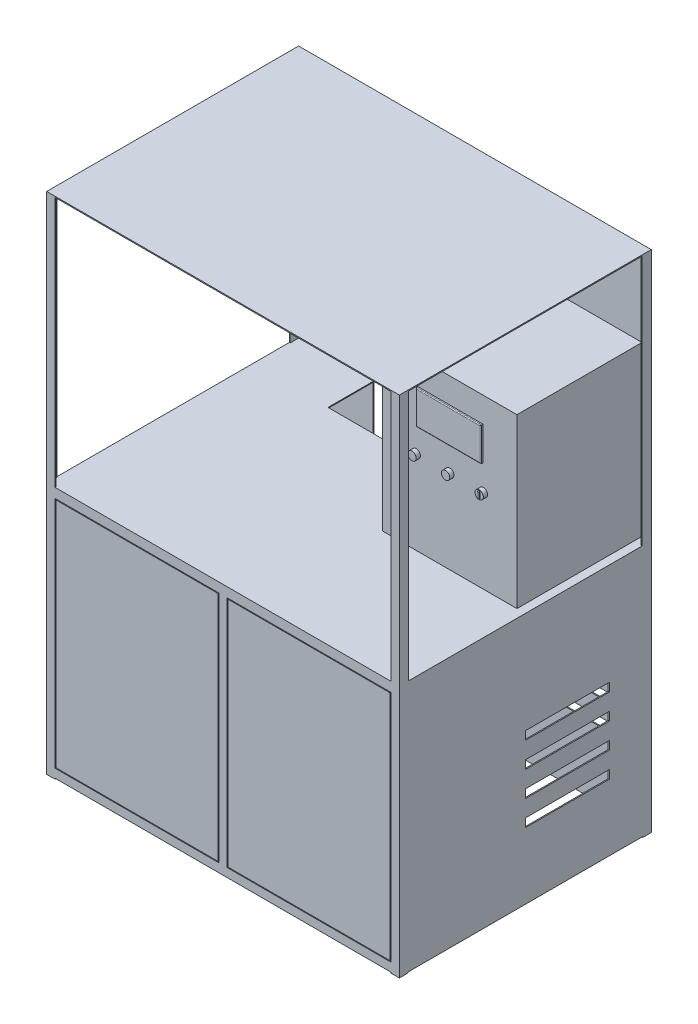
SolidWorks part; units mm, degrees
ref_plane "Front Plane" through (0, 0, 0) normal (0, 0, 1) x (1, 0, 0)
ref_plane "Top Plane" through (0, 0, 0) normal (0, 1, 0) x (1, 0, 0)
ref_plane "Right Plane" through (0, 0, 0) normal (1, 0, 0) x (0, 0, -1)
sketch "Sketch1" plane through (0, 0, 0) normal (0, 1, 0) x (1, 0, 0)
  line L1 (533.4, 381) -> (-533.4, 381)
  line L2 (533.4, 381) -> (533.4, -381)
  line L3 (533.4, -381) -> (-533.4, -381)
  line L4 (-533.4, 381) -> (-533.4, -381)
  line L5 (533.4, 381) -> (-533.4, -381) construction
  line L6 (533.4, -381) -> (-533.4, 381) construction
  point P0 (0, 0)
  dimension "D1" = 762
  dimension "D2" = 1066.8
extrude "Boss-Extrude1" add sketch "Sketch1" along normal blind 2.54 contours L1 L4 L3 L2
sketch "Sketch2" plane through (0, 2.54, 0) normal (0, 1, 0) x (1, 0, 0)
  line L0 (533.4, 381) -> (-533.4, 381) construction
  line L1 (-304.8, 381) -> (-101.6, 381)
  line L2 (-304.8, 381) -> (-304.8, 241.3)
  line L3 (-304.8, 241.3) -> (-101.6, 241.3)
  line L4 (-101.6, 381) -> (-101.6, 241.3)
  line L5 (-533.4, 381) -> (-533.4, -381) construction
  dimension "D1" = 139.7
  dimension "D2" = 203.2
  dimension "D3" = 228.6
extrude "Cut-Extrude1" cut sketch "Sketch2" against normal through all contours L3 L4 L1 L2
sketch "Sketch3" plane through (0, 0, 0) normal (0, -1, 0) x (1, 0, 0)
  line L1 (-533.4, 381) -> (-508, 381)
  line L2 (-533.4, 381) -> (-533.4, 355.6)
  line L3 (-533.4, 355.6) -> (-508, 355.6)
  line L4 (-508, 381) -> (-508, 355.6)
  line L5 (533.4, 381) -> (508, 381)
  line L6 (533.4, 381) -> (533.4, 355.6)
  line L7 (533.4, 355.6) -> (508, 355.6)
  line L8 (508, 381) -> (508, 355.6)
  line L9 (533.4, -381) -> (508, -381)
  line L10 (533.4, -381) -> (533.4, -355.6)
  line L11 (533.4, -355.6) -> (508, -355.6)
  line L12 (508, -381) -> (508, -355.6)
  line L13 (-533.4, -381) -> (-508, -381)
  line L14 (-533.4, -381) -> (-533.4, -355.6)
  line L15 (-533.4, -355.6) -> (-508, -355.6)
  line L16 (-508, -381) -> (-508, -355.6)
  dimension "D1" = 25.4
extrude "Boss-Extrude2" add sketch "Sketch3" along normal blind 762
sketch "Sketch4" plane through (0, 2.54, 0) normal (0, 1, 0) x (1, 0, 0)
  line L0 (533.4, 381) -> (-101.6, 381) construction
  line L5 (101.6, 381) -> (508, 381)
  line L6 (101.6, 381) -> (101.6, 0)
  line L7 (101.6, 0) -> (508, 0)
  line L8 (508, 381) -> (508, 0)
  line L9 (533.4, 381) -> (533.4, -381) construction
  dimension "D1" = 25.4
  dimension "D2" = 406.4
  dimension "D3" = 381
extrude "Boss-Extrude3" add sketch "Sketch4" along normal blind 508
sketch "Sketch5" plane through (0, 0, 0) normal (0, 0, 1) x (1, 0, 0)
  line L0 (101.6, 510.54) -> (101.6, 2.54) construction
  line L1 (101.6, 2.54) -> (508, 2.54) construction
  circle A0 centre (203.2, 256.54) radius 12.7
  circle A1 centre (304.8, 256.54) radius 12.7
  circle A2 centre (406.4, 256.54) radius 12.7
  dimension "D1" = 25.4
  dimension "D5" = 101.6
  dimension "D2" = 101.6
  dimension "D3" = 254
  dimension "D4" = 3
extrude "Boss-Extrude4" add sketch "Sketch5" along normal blind 12.7
sketch "Sketch6" plane through (0, 0, 12.7) normal (0, 0, 1) x (1, 0, 0)
  line L0 (406.4, 269.24) -> (406.4, 243.84) construction
  line L1 (404.4262, 266.7336) -> (408.3738, 266.7336)
  line L2 (408.3738, 266.7336) -> (408.3738, 246.4676)
  line L3 (408.3738, 246.4676) -> (404.4262, 246.4676)
  line L4 (404.4262, 266.7336) -> (404.4262, 246.4676)
  circle A0 centre (406.4, 256.54) radius 12.7 construction
  circle A1 centre (406.4, 256.54) radius 12.7 construction
  point P9 (0, 0)
  point P12 (0, 0)
  point P14 (406.4, 246.4676)
  point P15 (406.4, 266.7336)
  dimension "D1" = 2.5064
  dimension "D2" = 2.6276
  dimension "D3" = 1.9738
extrude "Boss-Extrude5" add sketch "Sketch6" along normal blind 3.175
fillet "Fillet1" radius 2.54 1 edges at (406.4, 266.7336, 15.875)
sketch "Sketch7" plane through (0, 0, 0) normal (0, 0, 1) x (1, 0, 0)
  line L0 (101.6, 510.54) -> (101.6, 2.54) construction
  line L1 (208.3389, 434.34) -> (405.1889, 434.34)
  line L2 (208.3389, 434.34) -> (208.3389, 332.74)
  line L3 (208.3389, 332.74) -> (405.1889, 332.74)
  line L4 (405.1889, 434.34) -> (405.1889, 332.74)
  line L5 (101.6, 510.54) -> (508, 510.54) construction
  dimension "D1" = 106.7389
  dimension "D2" = 76.2
  dimension "D3" = 101.6
  dimension "D4" = 196.85
extrude "Boss-Extrude6" add sketch "Sketch7" along normal blind 6.35
fillet "Fillet2" radius 2.54 4 edges at (208.3389, 383.54, 6.35) (306.7639, 332.74, 6.35) (405.1889, 383.54, 6.35) (306.7639, 434.34, 6.35)
sketch "Sketch8" plane through (0, 2.54, 0) normal (0, 1, 0) x (1, 0, 0)
  line L0 (-304.8, 381) -> (-304.8, 241.3) construction
  line L1 (-533.4, 381) -> (-304.8, 381)
  line L2 (-533.4, 381) -> (-533.4, 378.46)
  line L3 (-530.86, 378.46) -> (-304.8, 378.46)
  line L4 (-304.8, 381) -> (-304.8, 378.46)
  line L5 (533.4, 381) -> (533.4, -381) construction
  line L6 (-101.6, 381) -> (533.4, 381)
  line L7 (-101.6, 381) -> (-101.6, 378.46)
  line L8 (-101.6, 378.46) -> (533.4, 378.46)
  line L9 (533.4, 381) -> (533.4, 378.46)
  line L10 (0, -381) -> (0, 381) construction
  line L11 (-533.4, 378.46) -> (-530.86, 378.46)
  line L12 (-533.4, 378.46) -> (-533.4, 353.06)
  line L13 (-533.4, 353.06) -> (-530.86, 353.06)
  line L14 (-530.86, 378.46) -> (-530.86, 353.06)
  line L15 (533.4, -381) -> (-533.4, -381) construction
  line L16 (-533.4, 0) -> (533.4, 0) construction
  line L17 (-533.4, 381) -> (-533.4, -381) construction
  line L18 (530.86, 378.46) -> (530.86, 353.06)
  line L19 (-533.4, -381) -> (-508, -381)
  line L20 (-533.4, -381) -> (-533.4, -378.46)
  line L21 (-533.4, -378.46) -> (-508, -378.46)
  line L22 (-508, -381) -> (-508, -378.46)
  line L23 (-533.4, -353.06) -> (-530.86, -353.06)
  line L24 (-533.4, -353.06) -> (-533.4, -378.46)
  line L25 (-533.4, -378.46) -> (-530.86, -378.46)
  line L26 (-530.86, -353.06) -> (-530.86, -378.46)
  line L27 (533.4, 353.06) -> (530.86, 353.06)
  line L28 (533.4, 378.46) -> (533.4, 353.06)
  line L29 (533.4, 378.46) -> (530.86, 378.46)
  line L30 (533.4, 381) -> (533.4, 378.46)
  line L31 (530.86, -353.06) -> (530.86, -378.46)
  line L32 (533.4, -378.46) -> (530.86, -378.46)
  line L33 (533.4, -353.06) -> (533.4, -378.46)
  line L34 (533.4, -353.06) -> (530.86, -353.06)
  line L35 (508, -381) -> (508, -378.46)
  line L36 (533.4, -378.46) -> (508, -378.46)
  line L37 (533.4, -381) -> (533.4, -378.46)
  line L38 (533.4, -381) -> (508, -381)
  point P44 (0, 0)
  line M9 (101.6, 0) -> (101.6, 381)
  line M10 (101.6, 381) -> (-101.6, 381)
  line M11 (-101.6, 381) -> (-101.6, 241.3)
  line M13 (-304.8, 241.3) -> (-304.8, 381)
  line M14 (-304.8, 381) -> (-533.4, 381)
  line M15 (-533.4, 381) -> (-533.4, -381)
  line M16 (-533.4, -381) -> (533.4, -381)
  line M17 (533.4, -381) -> (533.4, 381)
  line M18 (533.4, 381) -> (508, 381)
  line M19 (508, 381) -> (508, 0)
  dimension "D1" = 2.54
  dimension "D2" = 25.4
  dimension "D3" = 2.54
  dimension "D4" = 25.4
  dimension "D5" = 25.4
extrude "Boss-Extrude7" add sketch "Sketch8" along normal blind 759.46 contours L11 L3 M15 M13 M14 | L14 L11 L13 M15 | L8 M19 M17 M18 | L27 L8 L18 M17 | L8 M11 M9 M10 | L32 L36 L35 M16 M17 | L34 L31 L32 M17 | L26 L23 L21 M15 | L22 L21 M16 M15 | L8 L6 M9 M19
sketch "Sketch9" plane through (0, 762, 0) normal (0, 1, 0) x (1, 0, 0)
  line L1 (-533.4, 381) -> (533.4, 381)
  line L2 (-533.4, 381) -> (-533.4, -381)
  line L3 (-533.4, -381) -> (533.4, -381)
  line L4 (533.4, 381) -> (533.4, -381)
extrude "Boss-Extrude8" add sketch "Sketch9" along normal blind 3.175
sketch "Sketch11" plane through (0, 0, 0) normal (0, -1, 0) x (1, 0, 0)
  line L0 (508, 381) -> (508, 355.6) construction
  line L1 (-508, 381) -> (508, 381)
  line L2 (-508, 381) -> (-508, 377.825)
  line L3 (-508, 377.825) -> (508, 377.825)
  line L4 (508, 381) -> (508, 377.825)
  line L5 (533.4, -355.6) -> (508, -355.6) construction
  line L6 (533.4, 355.6) -> (530.225, 355.6)
  line L7 (533.4, 355.6) -> (533.4, -355.6)
  line L8 (533.4, -355.6) -> (530.225, -355.6)
  line L9 (530.225, 355.6) -> (530.225, -355.6)
  line L10 (0, 381) -> (0, -381) construction
  line L11 (508, -381) -> (-101.6, -381) construction
  line L12 (-530.225, 355.6) -> (-530.225, -355.6)
  line L13 (-533.4, -355.6) -> (-530.225, -355.6)
  line L14 (-533.4, 355.6) -> (-533.4, -355.6)
  line L15 (-533.4, 355.6) -> (-530.225, 355.6)
  line L16 (-508, -381) -> (-508, -355.6) construction
  line L17 (-508, -377.825) -> (-304.8, -377.825)
  line L18 (-508, -377.825) -> (-508, -381)
  line L19 (-508, -381) -> (-304.8, -381)
  line L20 (-304.8, -377.825) -> (-304.8, -381)
  line L21 (-101.6, -381) -> (-101.6, -241.3) construction
  line L22 (-101.6, -377.825) -> (508, -377.825)
  line L23 (-101.6, -377.825) -> (-101.6, -381)
  line L24 (-101.6, -381) -> (508, -381)
  line L25 (508, -377.825) -> (508, -381)
  dimension "D1" = 3.175
  dimension "D2" = 3.175
  dimension "D3" = 3.175
extrude "Boss-Extrude10" add sketch "Sketch11" along normal blind 759.46
sketch "Sketch12" plane through (530.225, 0, 0) normal (-1, 0, 0) x (0, 0, 1)
  line L0 (-381, 765.175) -> (-381, -762) construction
  line L1 (0, -304.8) -> (-254, -304.8)
  line L2 (0, -304.8) -> (0, -330.2)
  line L3 (0, -330.2) -> (-254, -330.2)
  line L4 (-254, -304.8) -> (-254, -330.2)
  line L5 (0, -381) -> (-254, -381)
  line L6 (0, -381) -> (0, -406.4)
  line L7 (0, -406.4) -> (-254, -406.4)
  line L8 (-254, -381) -> (-254, -406.4)
  line L9 (0, -457.2) -> (-254, -457.2)
  line L10 (0, -457.2) -> (0, -482.6)
  line L11 (0, -482.6) -> (-254, -482.6)
  line L12 (-254, -457.2) -> (-254, -482.6)
  line L13 (0, -533.4) -> (-254, -533.4)
  line L14 (0, -533.4) -> (0, -558.8)
  line L15 (0, -558.8) -> (-254, -558.8)
  line L16 (-254, -533.4) -> (-254, -558.8)
  dimension "D1" = 304.8
  dimension "D2" = 127
  dimension "D3" = 25.4
  dimension "D4" = 254
  dimension "D6" = 50.8
  dimension "D5" = 4
extrude "Cut-Extrude3" cut sketch "Sketch12" against normal up to next
sketch "Sketch13" plane through (0, 0, -381) normal (0, 0, -1) x (-1, 0, 0)
  line L0 (-533.4, 765.175) -> (-533.4, -762) construction
  line L1 (-406.4, -304.8) -> (-152.4, -304.8)
  line L2 (-406.4, -304.8) -> (-406.4, -330.2)
  line L3 (-406.4, -330.2) -> (-152.4, -330.2)
  line L4 (-152.4, -304.8) -> (-152.4, -330.2)
  line L5 (-406.4, -381) -> (-152.4, -381)
  line L6 (-406.4, -381) -> (-406.4, -406.4)
  line L7 (-406.4, -406.4) -> (-152.4, -406.4)
  line L8 (-152.4, -381) -> (-152.4, -406.4)
  line L9 (-406.4, -457.2) -> (-152.4, -457.2)
  line L10 (-406.4, -457.2) -> (-406.4, -482.6)
  line L11 (-406.4, -482.6) -> (-152.4, -482.6)
  line L12 (-152.4, -457.2) -> (-152.4, -482.6)
  line L13 (-406.4, -533.4) -> (-152.4, -533.4)
  line L14 (-406.4, -533.4) -> (-406.4, -558.8)
  line L15 (-406.4, -558.8) -> (-152.4, -558.8)
  line L16 (-152.4, -533.4) -> (-152.4, -558.8)
  dimension "D1" = 25.4
  dimension "D2" = 304.8
  dimension "D3" = 127
  dimension "D4" = 254
  dimension "D6" = 50.8
  dimension "D5" = 4
extrude "Cut-Extrude4" cut sketch "Sketch13" against normal up to next
sketch "Sketch14" plane through (0, 0, 381) normal (0, 0, 1) x (1, 0, 0)
  line L0 (0, 0) -> (0, -759.46) construction
  line L1 (-508, -26.4565) -> (-12.7, -26.4565)
  line L2 (-508, -26.4565) -> (-508, -733.1778)
  line L3 (-508, -733.1778) -> (-12.7, -733.1778)
  line L4 (-12.7, -26.4565) -> (-12.7, -733.1778)
  line L5 (508, -759.46) -> (-508, -759.46) construction
  line L6 (508, 2.54) -> (-508, 2.54) construction
  line L7 (12.7, -26.4565) -> (12.7, -733.1778)
  line L8 (508, -733.1778) -> (12.7, -733.1778)
  line L9 (508, -26.4565) -> (508, -733.1778)
  line L10 (508, -26.4565) -> (12.7, -26.4565)
  line L11 (-505.46, -28.9965) -> (-15.24, -28.9965)
  line L12 (-15.24, -28.9965) -> (-15.24, -730.6378)
  line L13 (-505.46, -730.6378) -> (-15.24, -730.6378)
  line L14 (-505.46, -28.9965) -> (-505.46, -730.6378)
  line L15 (15.24, -28.9965) -> (15.24, -730.6378)
  line L16 (505.46, -730.6378) -> (15.24, -730.6378)
  line L17 (505.46, -28.9965) -> (505.46, -730.6378)
  line L18 (505.46, -28.9965) -> (15.24, -28.9965)
  dimension "D1" = 706.7213
  dimension "D2" = 495.3
  dimension "D3" = 28.9965
  dimension "D4" = 2.54
  dimension "D5" = 2.54
extrude "Cut-Extrude5" cut sketch "Sketch14" against normal blind 2.54
